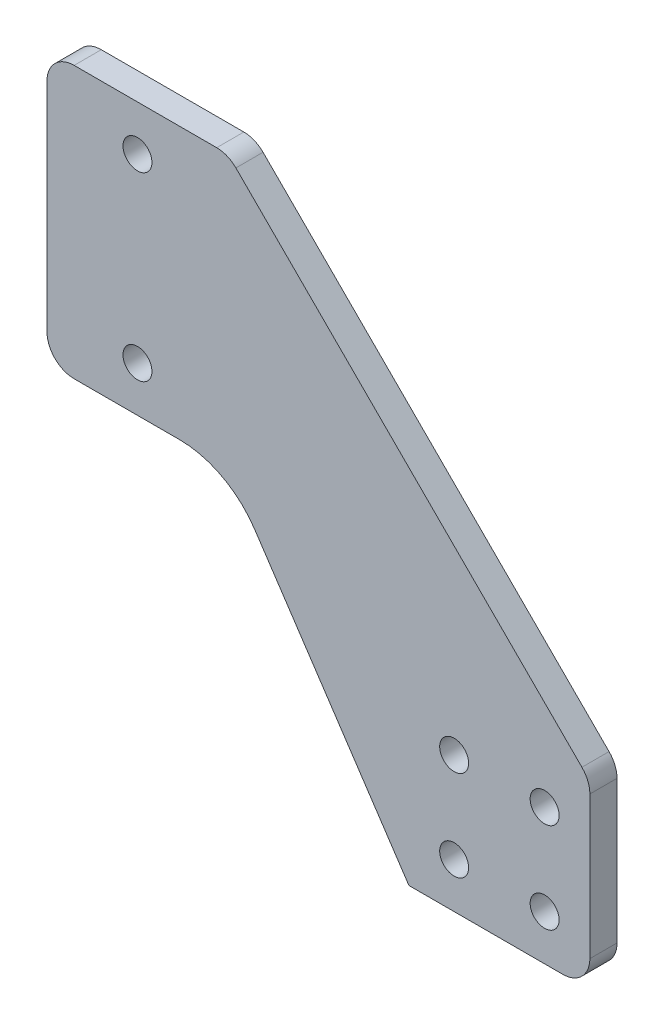
SolidWorks part; units mm, degrees
ref_plane "前视基准面" through (0, 0, 0) normal (0, 0, 1) x (1, 0, 0)
ref_plane "上视基准面" through (0, 0, 0) normal (0, 1, 0) x (1, 0, 0)
ref_plane "右视基准面" through (0, 0, 0) normal (1, 0, 0) x (0, 0, -1)
other "Configuration Table"
sketch "草图1" plane through (0, 0, 0) normal (0, 0, 1) x (1, 0, 0)
  line L0 (0, 0) -> (20, 0)
  line L1 (20, 0) -> (60, -40)
  line L2 (60, -40) -> (60, -60)
  line L3 (60, -60) -> (0, -60)
  line L4 (0, -60) -> (0, 0)
  line L5 (10, 0) -> (10, -60) construction
  line L6 (60, -50) -> (0, -50) construction
  line L7 (50, -60) -> (50, -30) construction
  circle A0 centre (10, -5) radius 1.6
  circle A1 centre (10, -25) radius 1.6
  circle A2 centre (55, -55) radius 1.6
  circle A3 centre (55, -45) radius 1.6
  circle A4 centre (45, -55) radius 1.6
  circle A5 centre (45, -45) radius 1.6
  dimension "D5" = 3.2
  dimension "D6" = 3.2
  dimension "D10" = 3.2
  dimension "D1" = 20
  dimension "D2" = 20
  dimension "D3" = 60
  dimension "D4" = 60
  dimension "D7" = 35
  dimension "D8" = 20
  dimension "D9" = 10
  dimension "D11" = 5
  dimension "D12" = 5
extrude "凸台-拉伸1" add sketch "草图1" along normal blind 3
sketch "草图2" plane through (0, 0, 3) normal (0, 0, 1) x (1, 0, 0)
  line L1 (0, 0) -> (0, -60) construction
  line L2 (0, -60) -> (60, -60) construction
  line L3 (40, -60) -> (0, -60)
  line L4 (0, -60) -> (0, -30)
  line L5 (0, -30) -> (20, -30)
  line L6 (20, -30) -> (40, -60)
  dimension "D1" = 40
  dimension "D2" = 30
  dimension "D3" = 20
extrude "切除-拉伸1" cut sketch "草图2" against normal through all
fillet "圆角1" radius 3 5 edges at (60, -60, 1.5) (60, -40, 1.5) (20, 0, 1.5) (0, 0, 1.5) (0, -30, 1.5)
fillet "圆角2" radius 10 1 edges at (20, -30, 1.5)
